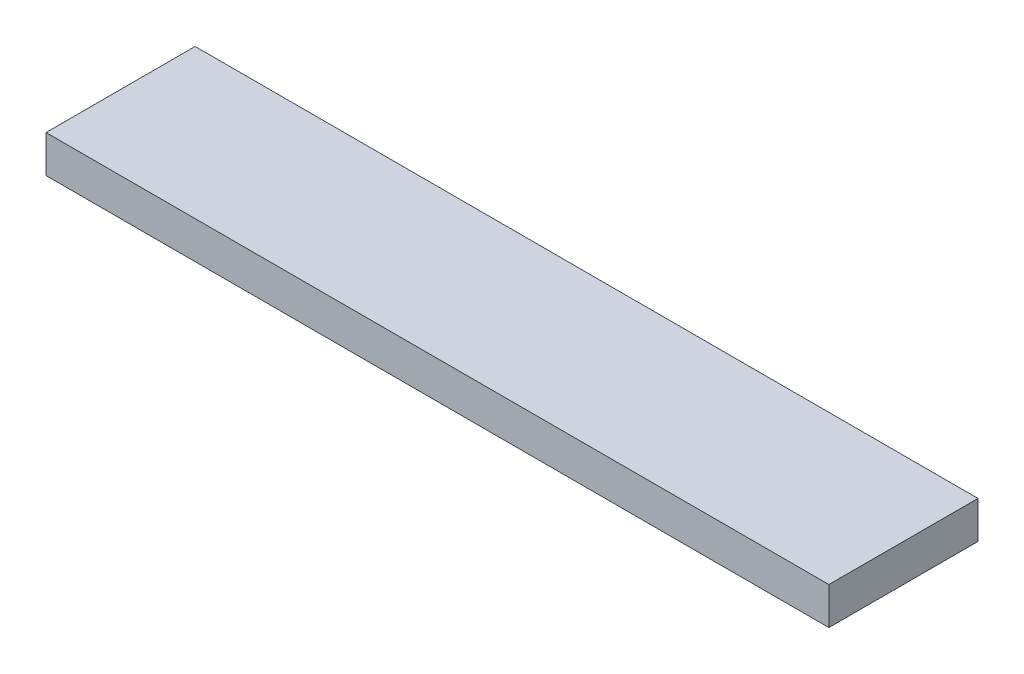
SolidWorks part; units mm, degrees
ref_plane "Front Plane" through (0, 0, 0) normal (0, 0, 1) x (1, 0, 0)
ref_plane "Top Plane" through (0, 0, 0) normal (0, 1, 0) x (1, 0, 0)
ref_plane "Right Plane" through (0, 0, 0) normal (1, 0, 0) x (0, 0, -1)
sketch "Sketch1" plane through (0, 0, 0) normal (0, 1, 0) x (1, 0, 0)
  line L1 (-66.675, -12.7) -> (66.675, -12.7)
  line L2 (-66.675, -12.7) -> (-66.675, 12.7)
  line L3 (-66.675, 12.7) -> (66.675, 12.7)
  line L4 (66.675, -12.7) -> (66.675, 12.7)
  line L5 (-66.675, -12.7) -> (66.675, 12.7) construction
  line L6 (-66.675, 12.7) -> (66.675, -12.7) construction
  point P0 (0, 0)
  dimension "D1" = 133.35
  dimension "D2" = 25.4
extrude "Boss-Extrude1" add sketch "Sketch1" along normal blind 6.35
equation "\"bus-bar-width\"= 1in"
equation "\"bus-bar-thickness\"= .25in"
equation "\"bus-bar-length\"= 5.25in"
equation "\"D1@Sketch1\"=\"bus-bar-length\""
equation "\"D2@Sketch1\"=\"bus-bar-width\""
equation "\"D1@Boss-Extrude1\"=\"bus-bar-thickness\""
